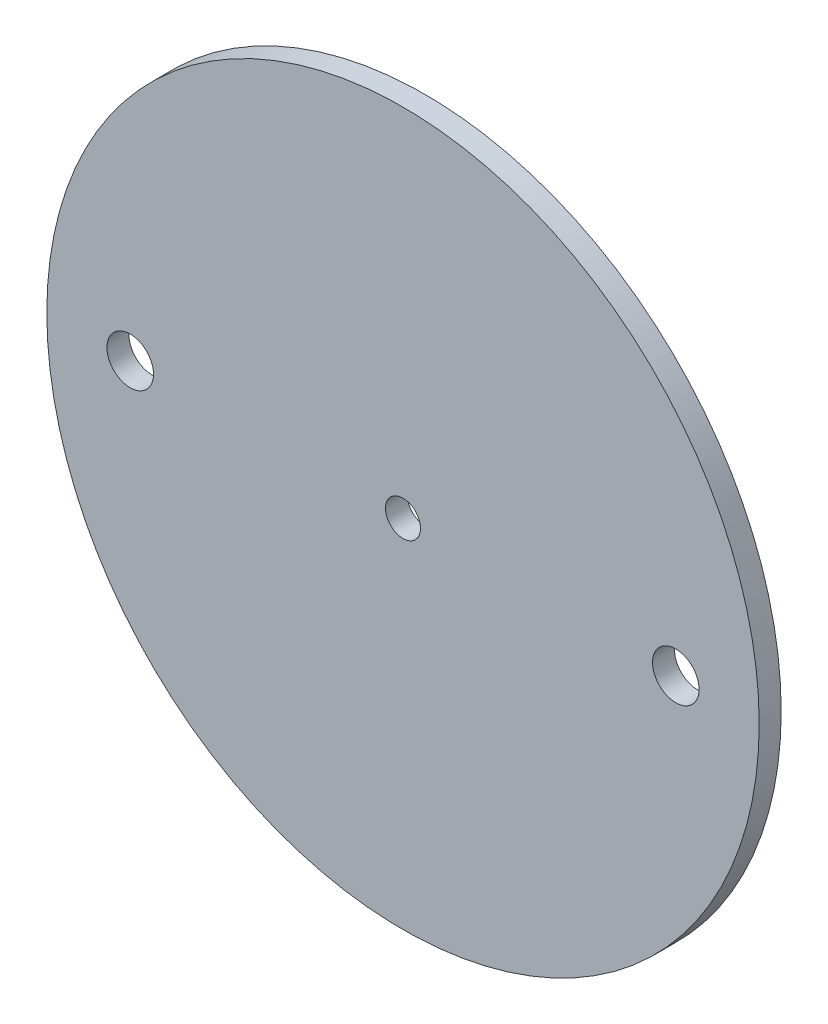
SolidWorks part; units mm, degrees
material "E-Glass Fiber"
ref_plane "Front Plane" through (0, 0, 0) normal (0, 0, 1) x (1, 0, 0)
ref_plane "Top Plane" through (0, 0, 0) normal (0, 1, 0) x (1, 0, 0)
ref_plane "Right Plane" through (0, 0, 0) normal (1, 0, 0) x (0, 0, -1)
sketch "Sketch1" plane through (0, 0, 0) normal (0, 0, 1) x (1, 0, 0)
  circle A0 centre (0, 0) radius 48.5394
  dimension "D1" = 97.0788
extrude "Boss-Extrude1" add sketch "Sketch1" along normal blind 2.9972
sketch "Sketch2" plane through (0, 0, 2.9972) normal (0, 0, 1) x (1, 0, 0)
  line L0 (-37.1729, 0) -> (0, 0) construction
  line L1 (0, 0) -> (37.1729, 0) construction
  circle A0 centre (0, 0) radius 2.3812
  circle A1 centre (37.1729, 0) radius 3.175
  circle A2 centre (-37.1729, 0) radius 3.175
  dimension "D1" = 4.7625
  dimension "D3" = 6.35
  dimension "D2" = 74.3458
extrude "Cut-Extrude1" cut sketch "Sketch2" against normal through all
